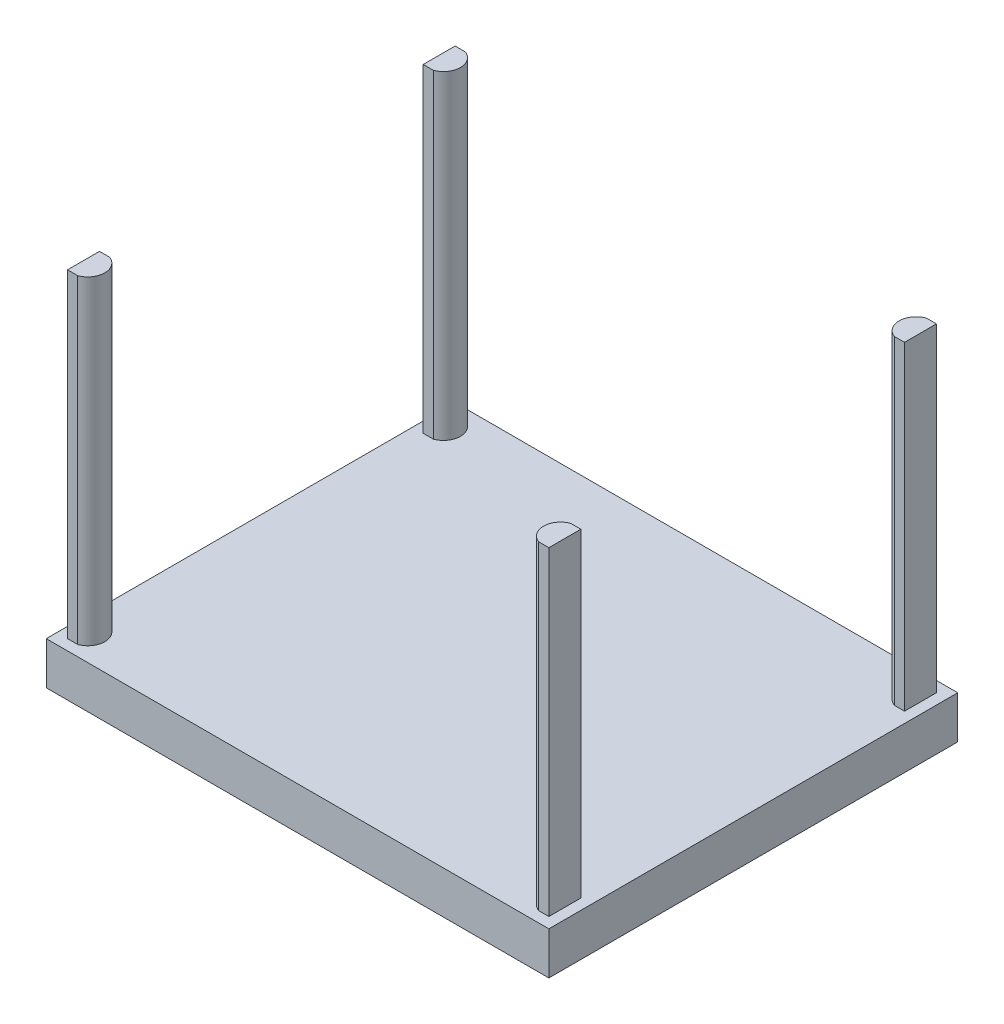
SolidWorks part; units mm, degrees
ref_plane "Piano frontale" through (0, 0, 0) normal (0, 0, 1) x (1, 0, 0)
ref_plane "Piano superiore" through (0, 0, 0) normal (0, 1, 0) x (1, 0, 0)
ref_plane "Piano destro" through (0, 0, 0) normal (1, 0, 0) x (0, 0, -1)
sketch "Schizzo2" plane through (0, 0, 0) normal (0, 1, 0) x (1, 0, 0)
  line L1 (-59, 48) -> (59, 48)
  line L2 (-59, 48) -> (-59, -48)
  line L3 (-59, -48) -> (59, -48)
  line L4 (59, 48) -> (59, -48)
  point P4 (0, 48)
  point P6 (-59, 0)
  dimension "D1" = 118
  dimension "D2" = 96
extrude "Estrusione-Estrusione1" add sketch "Schizzo2" along normal blind 20
sketch "Schizzo3" plane through (0, 0, 0) normal (0, 1, 0) x (1, 0, 0)
  line L8 (-49.2161, 28) -> (-54, 28)
  line L10 (-49.2161, 43) -> (-54, 43)
  line L11 (-54, 28) -> (-54, 43)
  line L12 (59, 48) -> (-59, 48) construction
  line L13 (-59, 48) -> (-59, -48) construction
  arc A0 (-49.2161, 43) -> (-49.2161, 28) centre (-52, 35.5) cw
  point P6 (-51.6081, 43)
  point P8 (-54, 35.5)
  point P9 (-44, 35.5)
  dimension "D1" = 8
  dimension "D4" = 10
  dimension "D2" = 5
  dimension "D3" = 15
  dimension "D5" = 5
  dimension "D6" = 4.7839
extrude "Estrusione-Estrusione2" add sketch "Schizzo3" along normal blind 170
mirror "Specchia3" about plane through (-59, 20, 48) normal (0, 0, -1) of bodies 102
mirror "Specchia2" about plane through (59, 20, -48) normal (-1, 0, 0) of bodies 105 103
